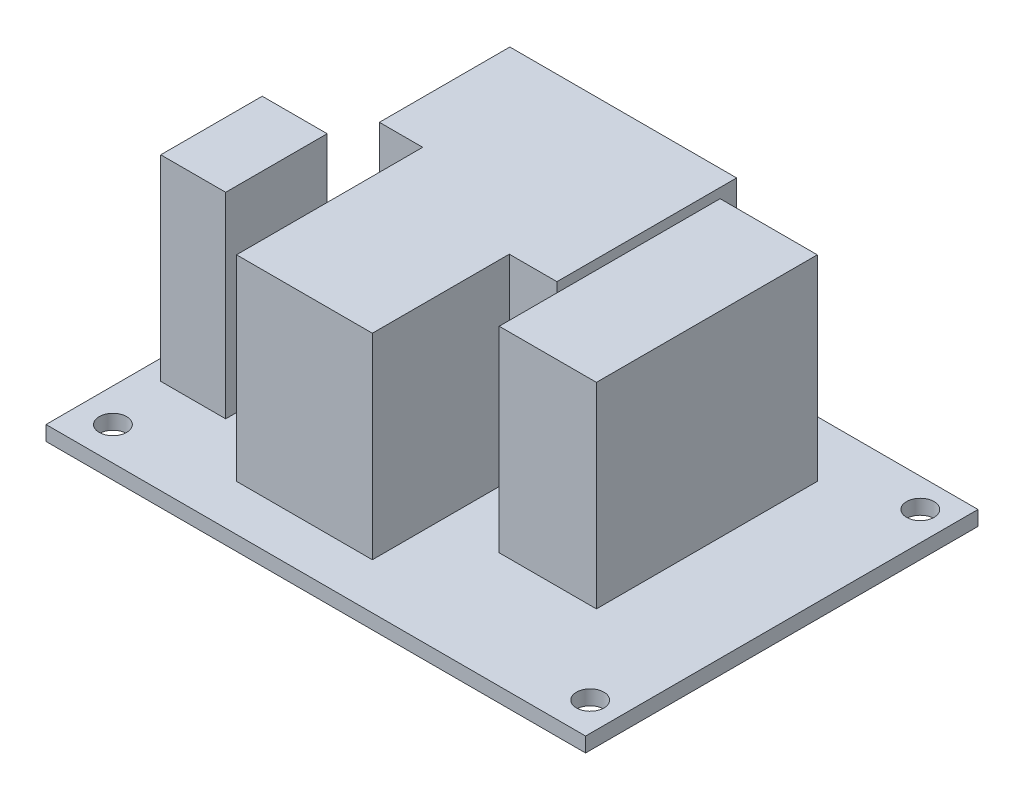
SolidWorks part; units mm, degrees
material "ABS PC"
ref_plane "Front Plane" through (0, 0, 0) normal (0, 0, 1) x (1, 0, 0)
ref_plane "Top Plane" through (0, 0, 0) normal (0, 1, 0) x (1, 0, 0)
ref_plane "Right Plane" through (0, 0, 0) normal (1, 0, 0) x (0, 0, -1)
sketch "Sketch1" plane through (0, 0, 0) normal (0, 1, 0) x (1, 0, 0)
  line L1 (-27.5, 20) -> (27.5, 20)
  line L2 (-27.5, 20) -> (-27.5, -20)
  line L3 (-27.5, -20) -> (27.5, -20)
  line L4 (27.5, 20) -> (27.5, -20)
  line L5 (-27.5, 20) -> (27.5, -20) construction
  line L6 (-27.5, -20) -> (27.5, 20) construction
  circle A0 centre (-24.09, 17.06) radius 1.4
  circle A1 centre (-24.09, -16.59) radius 1.4
  circle A2 centre (24.56, -16.59) radius 1.4
  circle A3 centre (24.56, 17.06) radius 1.4
  point P0 (0, 0)
  dimension "D3" = 2.8
  dimension "D1" = 40
  dimension "D2" = 55
  dimension "D4" = 33.65
  dimension "D5" = 48.65
  dimension "D6" = 2.94
  dimension "D7" = 2.94
extrude "Boss-Extrude1" add sketch "Sketch1" along normal blind 1.5
sketch "Sketch2" plane through (0, 1.5, 0) normal (0, 1, 0) x (1, 0, 0)
  line L0 (16.8317, 14.2895) -> (6.924, 14.2895)
  line L1 (6.924, 14.2895) -> (6.924, -8.2277)
  line L2 (6.924, -8.2277) -> (16.8317, -8.2277)
  line L3 (16.8317, -8.2277) -> (16.8317, 14.2895)
  line L4 (5.9305, 16.9641) -> (-17.1848, 16.9641)
  line L5 (-17.1848, 16.9641) -> (-17.1848, 3.6687)
  line L6 (-17.1848, 3.6687) -> (-12.7713, 3.6687)
  line L7 (-12.7713, 3.6687) -> (-12.7713, -15.3091)
  line L8 (-12.7713, -15.3091) -> (1.0758, -15.3091)
  line L9 (1.0758, -15.3091) -> (1.0758, -1.3516)
  line L10 (1.0758, -1.3516) -> (5.9305, -1.3516)
  line L11 (5.9305, -1.3516) -> (5.9305, 16.9641)
  line L12 (-18.8398, 0) -> (-25.4599, 0)
  line L13 (-25.4599, 0) -> (-25.4599, -10.344)
  line L14 (-25.4599, -10.344) -> (-18.8398, -10.344)
  line L15 (-18.8398, -10.344) -> (-18.8398, 0)
extrude "Boss-Extrude2" add sketch "Sketch2" along normal blind 20
